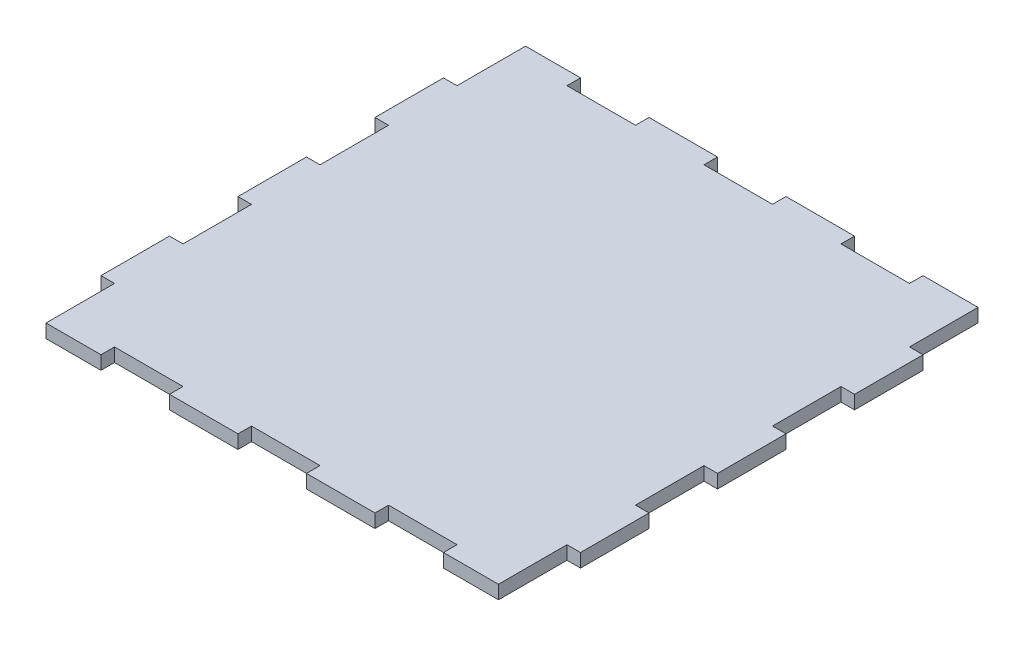
SolidWorks part; units mm, degrees
ref_plane "Front Plane" through (0, 0, 0) normal (0, 0, 1) x (1, 0, 0)
ref_plane "Top Plane" through (0, 0, 0) normal (0, 1, 0) x (1, 0, 0)
ref_plane "Right Plane" through (0, 0, 0) normal (1, 0, 0) x (0, 0, -1)
sketch "Sketch1" plane through (0, 0, 0) normal (0, 1, 0) x (1, 0, 0)
  line L48 (32.1429, 0) -> (32.1429, 6.35)
  line L49 (0, 0) -> (32.1429, 0)
  line L50 (0, 0) -> (0, 6.35)
  line L51 (0, 6.35) -> (32.1429, 6.35)
  line L52 (32.1429, 0) -> (32.1429, 6.35)
  line L53 (0, 0) -> (6.35, 0)
  line L54 (0, 0) -> (0, 32.1429)
  line L55 (0, 32.1429) -> (6.35, 32.1429)
  line L56 (6.35, 0) -> (6.35, 32.1429)
  line L57 (32.1429, 0) -> (64.2857, 0)
  line L58 (64.2857, 0) -> (64.2857, 6.35)
  line L59 (32.1429, 6.35) -> (64.2857, 6.35)
  line L60 (64.2857, 0) -> (64.2857, 6.35)
  line L61 (64.2857, 0) -> (96.4286, 0)
  line L62 (96.4286, 0) -> (96.4286, 6.35)
  line L63 (64.2857, 6.35) -> (96.4286, 6.35)
  line L64 (96.4286, 0) -> (96.4286, 6.35)
  line L65 (96.4286, 0) -> (128.5714, 0)
  line L66 (128.5714, 0) -> (128.5714, 6.35)
  line L67 (96.4286, 6.35) -> (128.5714, 6.35)
  line L72 (128.5714, 0) -> (128.5714, 6.35)
  line L73 (128.5714, 0) -> (160.7143, 0)
  line L74 (160.7143, 0) -> (160.7143, 6.35)
  line L75 (128.5714, 6.35) -> (160.7143, 6.35)
  line L76 (160.7143, 0) -> (160.7143, 6.35)
  line L77 (160.7143, 0) -> (192.8571, 0)
  line L78 (192.8571, 0) -> (192.8571, 6.35)
  line L79 (160.7143, 6.35) -> (192.8571, 6.35)
  line L80 (192.8571, 0) -> (192.8571, 6.35)
  line L81 (192.8571, 0) -> (225, 0)
  line L82 (225, 0) -> (225, 6.35)
  line L83 (192.8571, 6.35) -> (225, 6.35)
  line L84 (0, 32.1429) -> (0, 64.2857)
  line L85 (0, 32.1429) -> (6.35, 32.1429)
  line L86 (6.35, 32.1429) -> (6.35, 64.2857)
  line L87 (0, 64.2857) -> (6.35, 64.2857)
  line L88 (0, 64.2857) -> (0, 96.4286)
  line L89 (0, 64.2857) -> (6.35, 64.2857)
  line L90 (6.35, 64.2857) -> (6.35, 96.4286)
  line L91 (0, 96.4286) -> (6.35, 96.4286)
  line L98 (0, 96.4286) -> (0, 128.5714)
  line L99 (0, 96.4286) -> (6.35, 96.4286)
  line L100 (6.35, 96.4286) -> (6.35, 128.5714)
  line L101 (0, 128.5714) -> (6.35, 128.5714)
  line L102 (0, 128.5714) -> (0, 160.7143)
  line L103 (0, 128.5714) -> (6.35, 128.5714)
  line L104 (6.35, 128.5714) -> (6.35, 160.7143)
  line L105 (0, 160.7143) -> (6.35, 160.7143)
  line L106 (0, 160.7143) -> (0, 192.8571)
  line L107 (0, 160.7143) -> (6.35, 160.7143)
  line L108 (6.35, 160.7143) -> (6.35, 192.8571)
  line L109 (0, 192.8571) -> (6.35, 192.8571)
  line L110 (0, 192.8571) -> (0, 225)
  line L111 (0, 192.8571) -> (6.35, 192.8571)
  line L112 (6.35, 192.8571) -> (6.35, 225)
  line L113 (0, 225) -> (6.35, 225)
  line L114 (112.5, 0) -> (112.5, 671.069) construction
  line L115 (-187.856, 112.5) -> (254.8092, 112.5) construction
  line L116 (225, 32.1429) -> (218.65, 32.1429)
  line L117 (218.65, 0) -> (218.65, 32.1429)
  line L118 (225, 0) -> (218.65, 0)
  line L119 (225, 0) -> (225, 32.1429)
  line L120 (225, 192.8571) -> (218.65, 192.8571)
  line L121 (218.65, 192.8571) -> (218.65, 225)
  line L122 (225, 225) -> (218.65, 225)
  line L123 (225, 192.8571) -> (225, 225)
  line L124 (225, 160.7143) -> (218.65, 160.7143)
  line L125 (218.65, 160.7143) -> (218.65, 192.8571)
  line L126 (225, 192.8571) -> (218.65, 192.8571)
  line L127 (225, 160.7143) -> (225, 192.8571)
  line L128 (225, 32.1429) -> (218.65, 32.1429)
  line L129 (218.65, 32.1429) -> (218.65, 64.2857)
  line L130 (225, 64.2857) -> (218.65, 64.2857)
  line L131 (225, 32.1429) -> (225, 64.2857)
  line L132 (225, 128.5714) -> (218.65, 128.5714)
  line L133 (218.65, 128.5714) -> (218.65, 160.7143)
  line L134 (225, 160.7143) -> (218.65, 160.7143)
  line L135 (225, 128.5714) -> (225, 160.7143)
  line L136 (225, 96.4286) -> (218.65, 96.4286)
  line L137 (218.65, 96.4286) -> (218.65, 128.5714)
  line L138 (225, 128.5714) -> (218.65, 128.5714)
  line L139 (225, 96.4286) -> (225, 128.5714)
  line L140 (225, 64.2857) -> (218.65, 64.2857)
  line L141 (218.65, 64.2857) -> (218.65, 96.4286)
  line L142 (225, 96.4286) -> (218.65, 96.4286)
  line L143 (225, 64.2857) -> (225, 96.4286)
  line L144 (192.8571, 225) -> (225, 225)
  line L145 (225, 225) -> (225, 218.65)
  line L146 (192.8571, 218.65) -> (225, 218.65)
  line L147 (192.8571, 225) -> (192.8571, 218.65)
  line L148 (160.7143, 225) -> (192.8571, 225)
  line L149 (192.8571, 225) -> (192.8571, 218.65)
  line L150 (160.7143, 218.65) -> (192.8571, 218.65)
  line L151 (160.7143, 225) -> (160.7143, 218.65)
  line L152 (128.5714, 225) -> (160.7143, 225)
  line L153 (160.7143, 225) -> (160.7143, 218.65)
  line L154 (128.5714, 218.65) -> (160.7143, 218.65)
  line L155 (128.5714, 225) -> (128.5714, 218.65)
  line L156 (96.4286, 225) -> (128.5714, 225)
  line L157 (128.5714, 225) -> (128.5714, 218.65)
  line L158 (96.4286, 218.65) -> (128.5714, 218.65)
  line L159 (96.4286, 225) -> (96.4286, 218.65)
  line L160 (64.2857, 225) -> (96.4286, 225)
  line L161 (96.4286, 225) -> (96.4286, 218.65)
  line L162 (64.2857, 218.65) -> (96.4286, 218.65)
  line L163 (64.2857, 225) -> (64.2857, 218.65)
  line L164 (32.1429, 225) -> (64.2857, 225)
  line L165 (64.2857, 225) -> (64.2857, 218.65)
  line L166 (32.1429, 218.65) -> (64.2857, 218.65)
  line L167 (32.1429, 225) -> (32.1429, 218.65)
  line L168 (0, 218.65) -> (32.1429, 218.65)
  line L169 (32.1429, 225) -> (32.1429, 218.65)
  line L170 (0, 225) -> (32.1429, 225)
  line L171 (0, 225) -> (0, 218.65)
  point P4 (225, 197.6968)
  point P56 (112.5, 6.35)
  point P58 (6.35, 112.5)
  dimension "D3" = 225
  dimension "D4" = 225
  dimension "D5" = 6.35
  dimension "D2" = 7
  dimension "D1" = 7
extrude "Boss-Extrude1" add sketch "Sketch1" along normal blind 6.35 contours L168 L112 L108 L104 L100 L90 L86 L56 L51 L59 L63 L67 L75 L79 L83 L117 L129 L141 L137 L133 L125 L121 L146 L150 L154 L158 L162 L166 | L101 L98 L91 L100 | L87 L84 L55 L86 | L109 L106 L105 L108 | L56 L49 L48 L51 | L63 L58 L61 L62 | L75 L66 L73 L74 | L81 L117 L83 L78 | L116 L131 L130 L129 | L136 L139 L132 L137 | L124 L127 L120 L125 | L144 L147 L146 L121 | L152 L155 L154 L151 | L160 L163 L162 L159 | L170 L112 L168 L167
